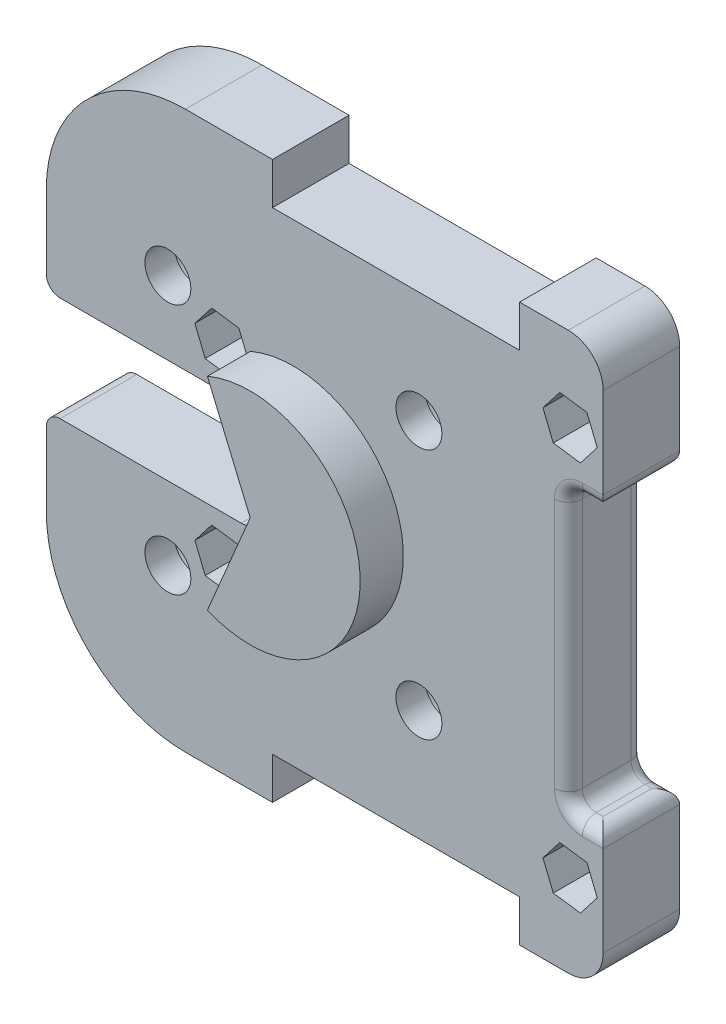
SolidWorks part; units mm, degrees
material "PEI"
ref_plane "前视基准面" through (0, 0, 0) normal (0, 0, 1) x (1, 0, 0)
ref_plane "上视基准面" through (0, 0, 0) normal (0, 1, 0) x (1, 0, 0)
ref_plane "右视基准面" through (0, 0, 0) normal (1, 0, 0) x (0, 0, -1)
sketch "草图1" plane through (0, 0, 0) normal (0, 0, 1) x (1, 0, 0)
  line L1 (-36.24, 26.4094) -> (43.76, 26.4094)
  line L2 (-36.24, 26.4094) -> (-36.24, -53.5906)
  line L3 (-36.24, -53.5906) -> (43.76, -53.5906)
  line L4 (43.76, 26.4094) -> (43.76, -53.5906)
  dimension "D1" = 80
  dimension "D2" = 80
extrude "凸台-拉伸1" add sketch "草图1" along normal blind 11
fillet "圆角1" radius 20 2 edges at (-36.24, -53.5906, 5.5) (-36.24, 26.4094, 5.5)
fillet "圆角2" radius 5 2 edges at (43.76, -53.5906, 5.5) (43.76, 26.4094, 5.5)
sketch "草图2" plane through (0, 0, 0) normal (0, 0, -1) x (-1, 0, 0)
  line L0 (36.24, 6.4094) -> (36.24, -33.5906) construction
  line L1 (36.24, -6.0906) -> (6.24, -6.0906)
  line L2 (36.24, -6.0906) -> (36.24, -21.0906)
  line L3 (36.24, -21.0906) -> (6.24, -21.0906)
  line L4 (6.24, -6.0906) -> (6.24, -21.0906)
  line L5 (-38.76, 26.4094) -> (16.24, 26.4094) construction
  line L6 (16.24, -53.5906) -> (-38.76, -53.5906) construction
  dimension "D1" = 32.5
  dimension "D2" = 32.5
  dimension "D3" = 30
extrude "切除-拉伸1" cut sketch "草图2" against normal blind 11
fillet "圆角3" radius 2 4 edges at (-6.24, -6.0906, 5.5) (-6.24, -21.0906, 5.5) (-36.24, -21.0906, 5.5) (-36.24, -6.0906, 5.5)
sketch "草图3" plane through (0, 0, 11) normal (0, 0, 1) x (1, 0, 0)
  line L0 (38.76, 26.4094) -> (-16.24, 26.4094) construction
  line L1 (-3.74, 26.4094) -> (31.76, 26.4094)
  line L2 (-3.74, 26.4094) -> (-3.74, 20.4094)
  line L3 (-3.74, 20.4094) -> (31.76, 20.4094)
  line L4 (31.76, 26.4094) -> (31.76, 20.4094)
  line L5 (-36.24, 6.4094) -> (-36.24, -4.0906) construction
  line L6 (43.76, -48.5906) -> (43.76, 21.4094) construction
  dimension "D1" = 32.5
  dimension "D2" = 12
  dimension "D3" = 6
extrude "切除-拉伸2" cut sketch "草图3" against normal blind 11
sketch "草图4" plane through (0, 0, 11) normal (0, 0, 1) x (1, 0, 0)
  line L0 (-16.24, -53.5906) -> (38.76, -53.5906) construction
  line L1 (-3.74, -47.5906) -> (31.76, -47.5906)
  line L2 (-3.74, -47.5906) -> (-3.74, -53.5906)
  line L3 (-3.74, -53.5906) -> (31.76, -53.5906)
  line L4 (31.76, -47.5906) -> (31.76, -53.5906)
  line L5 (-36.24, -23.0906) -> (-36.24, -33.5906) construction
  line L6 (43.76, -48.5906) -> (43.76, 21.4094) construction
  dimension "D1" = 32.5
  dimension "D2" = 12
  dimension "D3" = 6
extrude "切除-拉伸3" cut sketch "草图4" against normal blind 11
sketch "草图5" plane through (0, 0, 11) normal (0, 0, 1) x (1, 0, 0)
  line L0 (43.76, -48.5906) -> (43.76, 21.4094) construction
  line L1 (43.76, 6.4094) -> (38.76, 6.4094)
  line L2 (43.76, 6.4094) -> (43.76, -33.5906)
  line L3 (43.76, -33.5906) -> (38.76, -33.5906)
  line L4 (38.76, 6.4094) -> (38.76, -33.5906)
  line L5 (38.76, 26.4094) -> (31.76, 26.4094) construction
  dimension "D1" = 20
  dimension "D2" = 20
  dimension "D3" = 5
extrude "切除-拉伸4" cut sketch "草图5" against normal blind 11
fillet "圆角4" radius 2 10 edges at (41.26, -33.5906, 0) (41.26, -33.5906, 11) (38.76, -13.5906, 0) (38.76, -13.5906, 11) (43.76, -33.5906, 5.5) (38.76, -33.5906, 5.5) (41.26, 6.4094, 0) (41.26, 6.4094, 11) (38.76, 6.4094, 5.5) (43.76, 6.4094, 5.5)
sketch "草图8" plane through (0, 0, 11) normal (0, 0, 1) x (1, 0, 0)
  line L0 (43.76, -48.5906) -> (43.76, -35.5906) construction
  line L1 (31.76, -53.5906) -> (38.76, -53.5906) construction
  line L2 (43.76, 8.4094) -> (43.76, 21.4094) construction
  line L4 (38.76, 26.4094) -> (31.76, 26.4094) construction
  line L5 (-16.24, -53.5906) -> (-3.74, -53.5906) construction
  line L6 (-36.24, -23.0906) -> (-36.24, -33.5906) construction
  line L7 (-3.74, 26.4094) -> (-16.24, 26.4094) construction
  line L8 (-36.24, 6.4094) -> (-36.24, -4.0906) construction
  circle A0 centre (39.01, -41.5906) radius 1.9
  circle A1 centre (-10.99, -27.0906) radius 1.9
  circle A2 centre (-10.99, -0.0906) radius 1.9
  circle A3 centre (39.01, 14.4094) radius 1.9
  dimension "D1" = 4.75
  dimension "D2" = 12
  dimension "D3" = 4.75
  dimension "D4" = 12
  dimension "D5" = 26.5
  dimension "D6" = 25.25
  dimension "D7" = 26.5
  dimension "D8" = 25.25
extrude "切除-拉伸5" cut sketch "草图8" against normal blind 11
sketch "草图9" plane through (0, 0, 11) normal (0, 0, 1) x (1, 0, 0)
  line L0 (-14.8904, -26.5508) -> (-13.4076, -30.1985)
  line L1 (37.5272, -37.9429) -> (35.1096, -41.0508)
  line L2 (35.1096, -41.0508) -> (36.5924, -44.6985)
  line L3 (36.5924, -44.6985) -> (40.4928, -45.2382)
  line L4 (40.4928, -45.2382) -> (42.9103, -42.1303)
  line L5 (42.9103, -42.1303) -> (41.4276, -38.4826)
  line L6 (41.4276, -38.4826) -> (37.5272, -37.9429)
  line L7 (-9.5072, -30.7382) -> (-7.0897, -27.6303)
  line L8 (-7.0897, -27.6303) -> (-8.5724, -23.9826)
  line L9 (-8.5724, -23.9826) -> (-12.4728, -23.4429)
  line L10 (-12.4728, -23.4429) -> (-14.8904, -26.5508)
  line L11 (-13.4076, -30.1985) -> (-9.5072, -30.7382)
  line L12 (-8.5724, 3.0174) -> (-12.4728, 3.5571)
  line L13 (-12.4728, 3.5571) -> (-14.8904, 0.4492)
  line L14 (-7.0897, -0.6303) -> (-8.5724, 3.0174)
  line L15 (-13.4076, -3.1985) -> (-9.5072, -3.7382)
  line L16 (-14.8904, 0.4492) -> (-13.4076, -3.1985)
  line L17 (-9.5072, -3.7382) -> (-7.0897, -0.6303)
  line L18 (36.5924, 11.3015) -> (40.4928, 10.7618)
  line L19 (40.4928, 10.7618) -> (42.9103, 13.8697)
  line L20 (35.1096, 14.9492) -> (36.5924, 11.3015)
  line L21 (37.5272, 18.0571) -> (35.1096, 14.9492)
  line L22 (41.4276, 17.5174) -> (37.5272, 18.0571)
  line L23 (42.9103, 13.8697) -> (41.4276, 17.5174)
  circle A0 centre (39.01, -41.5906) radius 3.41 construction
  circle A1 centre (-10.99, -27.0906) radius 3.41 construction
  circle A2 centre (-10.99, -0.0906) radius 3.41 construction
  circle A3 centre (39.01, 14.4094) radius 3.41 construction
extrude "切除-拉伸6" cut sketch "草图9" against normal blind 8.5
sketch "草图10" plane through (0, 0, 11) normal (0, 0, 1) x (1, 0, 0)
  line L0 (-6.24, -13.5906) -> (36.76, -13.5906) construction
  line L1 (-6.24, -8.0906) -> (-6.24, -19.0906) construction
  line L2 (36.76, -31.5906) -> (36.76, 4.4094) construction
  line L3 (-0.74, -13.5906) -> (-6.8959, 0.9609)
  line L5 (-0.74, -13.5906) -> (-6.8959, -28.1421)
  circle A0 centre (-0.74, -13.5906) radius 37.5 construction
  arc A1 (-6.8959, -28.1421) -> (-6.8959, 0.9609) centre (-0.74, -13.5906) ccw
  dimension "D1" = 0
  dimension "D2" = 37.5
sketch "草图11" plane through (0, 0, 11) normal (0, 0, 1) x (1, 0, 0)
  line L0 (17.2912, 4.4407) -> (-18.7712, -31.6218) construction
  line L1 (17.2912, -31.6218) -> (-18.7712, 4.4407) construction
  line L2 (-26.24, -13.5906) -> (36.76, -13.5906) construction
  line L3 (36.76, -31.5906) -> (36.76, 4.4094) construction
  circle A0 centre (-0.74, -13.5906) radius 25.5 construction
  circle A1 centre (-18.7712, 4.4407) radius 2.5
  circle A2 centre (17.2912, 4.4407) radius 2.5
  circle A3 centre (17.2912, -31.6218) radius 2.5
  circle A4 centre (-18.7712, -31.6218) radius 2.5
  dimension "D1" = 45
  dimension "D2" = 45
extrude "凸台-拉伸2" add sketch "草图10" along normal blind 6.2
hole_wizard "打孔尺寸(%根据)内六角圆柱头螺钉的类型2" positions "草图15" profile "草图14" counterbore size "M6" standard "GB" end condition up to next
sketch "草图15" plane through (0, 0, 0) normal (0, 0, -1) x (-1, 0, 0)
  point P0 (-17.2912, 4.4407)
  point P3 (18.7712, 4.4407)
  point P6 (18.7712, -31.6218)
  point P9 (-17.2912, -31.6218)
sketch "草图14" plane through (17.2912, 4.4407, 0) normal (1, 0, 0) x (0, 1, 0)
  line L0 (0, 0) -> (0, 11)
  line L1 (0, 11) -> (3.3, 11)
  line L3 (3.3, 11) -> (3.3, 6.8)
  line L4 (3.3, 6.8) -> (5.5, 6.8)
  line L5 (5.5, 6.8) -> (5.5, 0)
  line L7 (5.5, 0) -> (0, 0)
  line L11 (0, -6.35) -> (0, 107.95) construction
  dimension "通孔孔直径" = 6.6
  dimension "通孔孔深度" = 11
  dimension "柱形沉头孔直径" = 11
  dimension "柱形沉头孔深度" = 6.8
